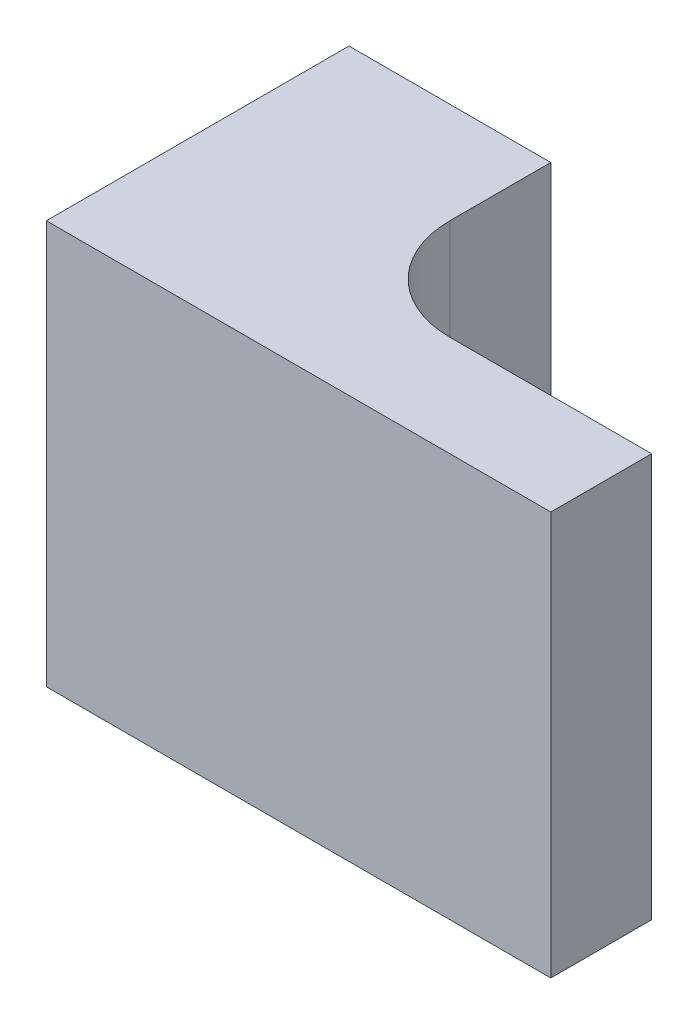
SolidWorks part; units mm, degrees
ref_plane "Přední rovina" through (0, 0, 0) normal (0, 0, 1) x (1, 0, 0)
ref_plane "Horní rovina" through (0, 0, 0) normal (0, 1, 0) x (1, 0, 0)
ref_plane "Pravá rovina" through (0, 0, 0) normal (1, 0, 0) x (0, 0, -1)
sketch "Sketch2" plane through (0, 0, 0) normal (0, 1, 0) x (1, 0, 0)
  line L0 (0, 0) -> (0, -5)
  line L1 (5, -10) -> (15, -10)
  line L2 (15, -10) -> (15, -15)
  line L3 (15, -15) -> (-10, -15)
  line L4 (-10, -15) -> (-10, 0)
  line L5 (-10, 0) -> (0, 0)
  arc A0 (0, -5) -> (5, -10) centre (5, -5) ccw
  dimension "D2" = 5
  dimension "D1" = 10
  dimension "D3" = 10
  dimension "D4" = 5
  dimension "D5" = 5
extrude "Boss-Extrude1" add sketch "Sketch2" along normal blind 20
equation "\"R\"= 5"
